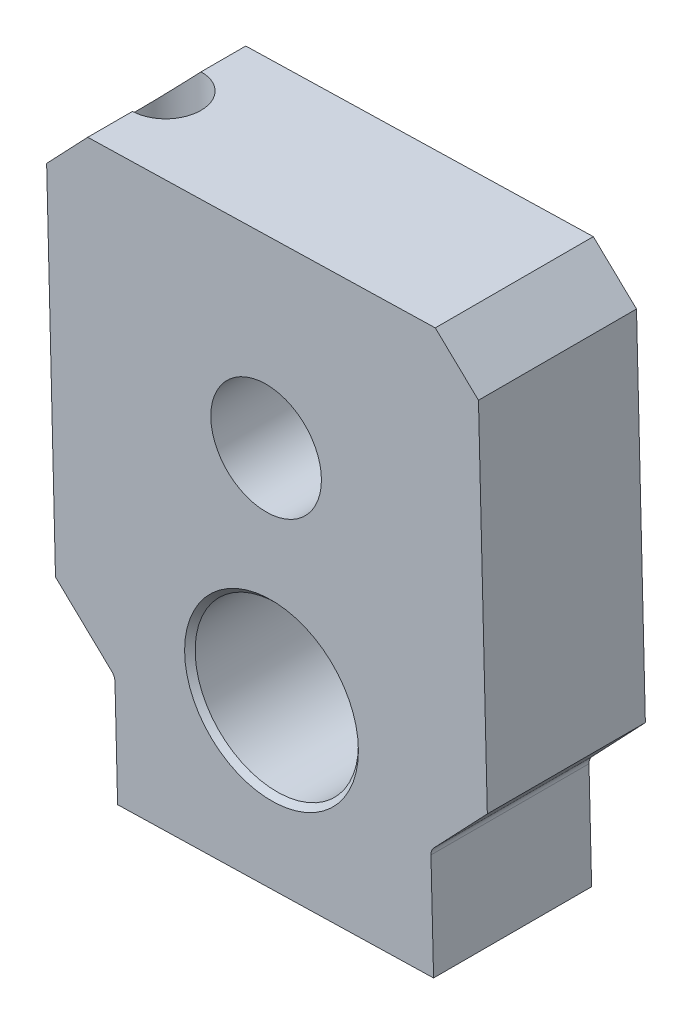
SolidWorks part; units mm, degrees
ref_plane "Front Plane" through (0, 0, 0) normal (0, 0, 1) x (1, 0, 0)
ref_plane "Top Plane" through (0, 0, 0) normal (0, 1, 0) x (1, 0, 0)
ref_plane "Right Plane" through (0, 0, 0) normal (1, 0, 0) x (0, 0, -1)
sketch "Sketch1" plane through (0, 0, 0) normal (0, 0, 1) x (1, 0, 0)
  line L0 (20.996, -19.5741) -> (20.056, 18.0071)
  line L2 (20.056, 18.0071) -> (-20.9311, 16.982)
  line L3 (-19.9912, -20.5992) -> (-20.9311, 16.982)
  line L4 (20.921, -16.575) -> (20.0662, 17.6001) construction
  line L5 (-19.9912, -20.5992) -> (-20.846, 13.5759) construction
  line L6 (-17.5251, 17.0672) -> (16.65, 17.9219) construction
  line L7 (-14.0952, -36.3638) -> (15.8954, -35.6137) construction
  line L8 (20.996, -19.5741) -> (15.9207, -24.9097) construction
  line L9 (15.8954, -35.6137) -> (15.6456, -25.6239) construction
  line L10 (-14.3451, -26.374) -> (-14.0952, -36.3638) construction
  line L11 (-14.6555, -25.6745) -> (-19.9912, -20.5992) construction
  line L12 (20.996, -19.5741) -> (15.9207, -24.9097)
  line L13 (15.8954, -35.6137) -> (15.6456, -25.6239)
  line L14 (-14.0952, -36.3638) -> (15.8954, -35.6137)
  line L15 (-14.3451, -26.374) -> (-14.0952, -36.3638)
  line L16 (-14.6555, -25.6745) -> (-19.9912, -20.5992)
  circle A0 centre (0, 0) radius 5.25
  arc A1 (15.9207, -24.9097) -> (15.6456, -25.6239) centre (16.6452, -25.5989) ccw construction
  arc A2 (-14.3451, -26.374) -> (-14.6555, -25.6745) centre (-15.3447, -26.399) ccw construction
  arc A3 (15.9207, -24.9097) -> (15.6456, -25.6239) centre (16.6452, -25.5989) ccw
  arc A4 (-14.3451, -26.374) -> (-14.6555, -25.6745) centre (-15.3447, -26.399) ccw
  circle A5 centre (0.5126, -20.4936) radius 7.75
  dimension "D1" = 10.5
  dimension "D2" = 15.5
extrude "Boss-Extrude2" add sketch "Sketch1" along normal blind 15
sketch "Sketch3" plane through (0, 0, 0) normal (0, 0, -1) x (-1, 0, 0)
  circle A0 centre (0, 0) radius 11.15
  dimension "D1" = 22.3
extrude "Cut-Extrude2" cut sketch "Sketch3" against normal blind 3
chamfer "Chamfer1" distance 4 angle 45 2 edges at (20.056, 18.0071, 7.5) (-20.9311, 16.982, 7.5)
chamfer "Chamfer2" distance 0.5 angle 45 2 edges at (8.2626, -20.4936, 15) (8.2626, -20.4936, 0)
sketch "Sketch4" plane through (-0.4375, 17.4945, 0) normal (-0.025, 0.9997, 0) x (0.9997, 0.025, 0)
  line L0 (-16.5, 0) -> (-16.5, -15) construction
  circle A0 centre (-16.5, -7.5) radius 3.25
  dimension "D1" = 6.5
extrude "Cut-Extrude3" cut sketch "Sketch4" against normal up to surface (38.3429 mm away)
